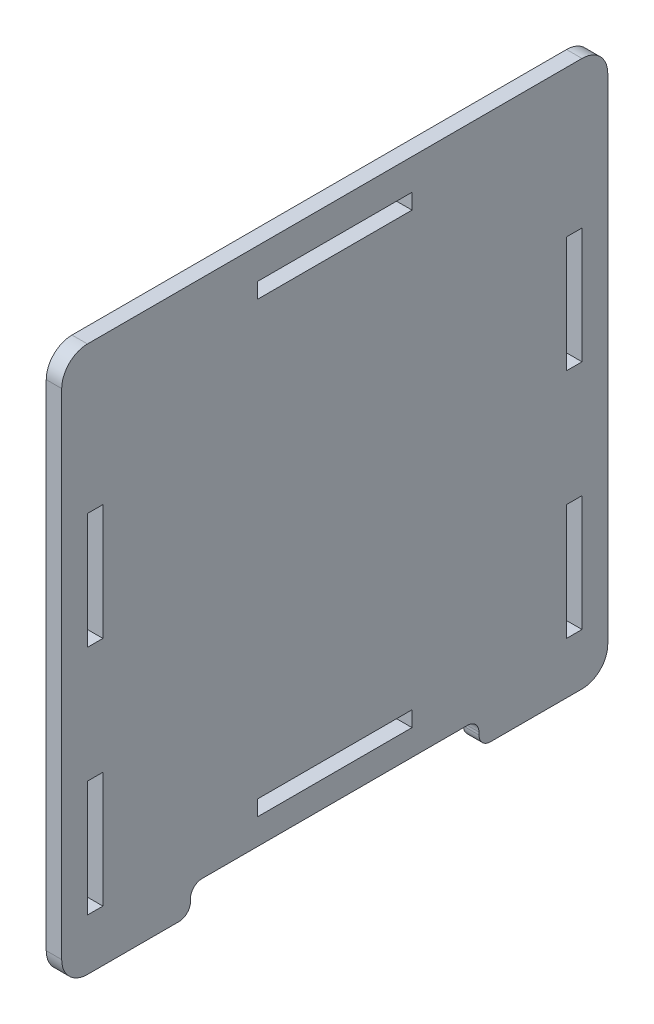
SolidWorks part; units mm, degrees
ref_plane "Front Plane" through (0, 0, 0) normal (0, 0, 1) x (1, 0, 0)
ref_plane "Top Plane" through (0, 0, 0) normal (0, 1, 0) x (1, 0, 0)
ref_plane "Right Plane" through (0, 0, 0) normal (1, 0, 0) x (0, 0, -1)
sketch "Sketch1" plane through (0, 0, 0) normal (1, 0, 0) x (0, 0, -1)
  line L2 (0, 0) -> (0, 19.5)
  line L4 (90, 0) -> (90, 19.5)
  line L14 (30, 84) -> (60, 84)
  line L18 (30, 84) -> (30, 87)
  line L20 (60, 87) -> (60, 84)
  line L23 (30, 0) -> (60, 0)
  line L25 (0, 0) -> (0, -3)
  line L27 (30, 0) -> (30, -3)
  line L29 (60, 0) -> (60, -3)
  line L31 (90, 0) -> (90, -3)
  line L32 (90, 42) -> (90, 64.5)
  line L35 (90, 64.5) -> (93, 64.5)
  line L37 (90, 42) -> (93, 42)
  line L39 (90, 19.5) -> (93, 19.5)
  line L43 (0, 64.5) -> (-3, 64.5)
  line L45 (0, 42) -> (-3, 42)
  line L47 (0, 19.5) -> (-3, 19.5)
  line L49 (0, 42) -> (0, 64.5)
  line L50 (75.25, -13) -> (93, -13)
  line L51 (-3, 93) -> (93, 93)
  line L52 (-8, 88) -> (-8, -8)
  line L53 (-3, -13) -> (14.75, -13)
  line L54 (98, 88) -> (98, -8)
  line L56 (17, -10.75) -> (17, -10.25)
  line L57 (19.25, -8) -> (70.75, -8)
  line L58 (73, -10.75) -> (73, -10.25)
  line L59 (30, 87) -> (60, 87)
  line L60 (-3, 42) -> (-3, 64.5)
  line L61 (93, 64.5) -> (93, 42)
  line L62 (-3, 19.5) -> (-3, -3)
  line L63 (0, -3) -> (-3, -3)
  line L64 (90, -3) -> (93, -3)
  line L65 (93, 19.5) -> (93, -3)
  line L66 (30, -3) -> (60, -3)
  arc A0 (-8, -8) -> (-3, -13) centre (-3, -8) ccw
  arc A1 (93, -13) -> (98, -8) centre (93, -8) ccw
  arc A2 (93, 93) -> (98, 88) centre (93, 88) cw
  arc A3 (-3, 93) -> (-8, 88) centre (-3, 88) ccw
  arc A4 (70.75, -8) -> (73, -10.25) centre (70.75, -10.25) cw
  arc A5 (75.25, -13) -> (73, -10.75) centre (75.25, -10.75) cw
  arc A6 (17, -10.25) -> (19.25, -8) centre (19.25, -10.25) cw
  arc A7 (14.75, -13) -> (17, -10.75) centre (14.75, -10.75) ccw
  point P37 (17, -10.5)
  point P50 (17, -8)
  point P53 (17, -13)
  dimension "D4" = 5
  dimension "D10" = 2.25
  dimension "D2" = 90
  dimension "D3" = 30
  dimension "D5" = 30
  dimension "D6" = 30
  dimension "D7" = 3
  dimension "D8" = 3
  dimension "D9" = 3
  dimension "D11" = 3
  dimension "D13" = 22.5
  dimension "D14" = 22.5
  dimension "D15" = 19.5
  dimension "D16" = 3
  dimension "D17" = 3
  dimension "D20" = 22.5
  dimension "D21" = 22.5
  dimension "D22" = 3
  dimension "D23" = 19.5
  dimension "D24" = 30
  dimension "D29" = 25
  dimension "D30" = 25
  dimension "D31" = 5
extrude "Boss-Extrude1" add sketch "Sketch1" along normal blind 3
